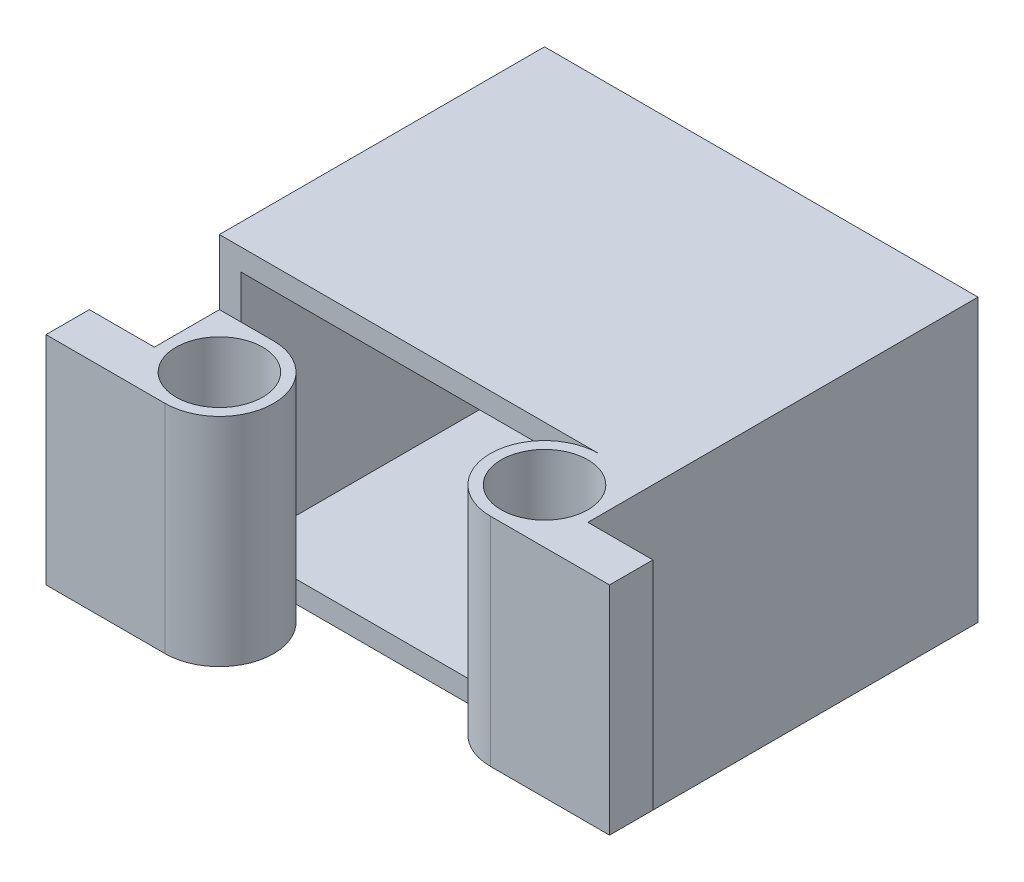
SolidWorks part; units mm, degrees
ref_plane "정면" through (0, 0, 0) normal (0, 0, 1) x (1, 0, 0)
ref_plane "윗면" through (0, 0, 0) normal (0, 1, 0) x (1, 0, 0)
ref_plane "우측면" through (0, 0, 0) normal (1, 0, 0) x (0, 0, -1)
sketch "스케치1" plane through (0, 0, 0) normal (0, 0, 1) x (1, 0, 0)
  line L1 (-10, -6.5) -> (10, -6.5)
  line L2 (-10, -6.5) -> (-10, 6.5)
  line L3 (-10, 6.5) -> (10, 6.5)
  line L4 (10, -6.5) -> (10, 6.5)
  line L5 (-10, -6.5) -> (10, 6.5) construction
  line L6 (-10, 6.5) -> (10, -6.5) construction
  point P0 (0, 0)
  dimension "D1" = 13
  dimension "D2" = 20
extrude "보스-돌출1" add sketch "스케치1" along normal blind 15
shell "쉘1" thickness 1
ref_plane "평면1" through (0, 3.5, 0) normal (0, 1, 0) x (1, 0, 0)
sketch "스케치2" plane through (0, 3.5, 0) normal (0, 1, 0) x (1, 0, 0)
  line L0 (10, -15) -> (-10, -15) construction
  line L2 (-10, -15) -> (-10, 0) construction
  line L3 (-10, -15) -> (-10, -17.5)
  line L5 (-10, -17.5) -> (-10, -20)
  line L6 (-10, -20) -> (-7.5, -20)
  line L9 (-10, -15) -> (-7.5, -15)
  circle A0 centre (-7.5, -17.5) radius 2.5
  circle A2 centre (-7.5, -17.5) radius 2
  dimension "D2" = 5
  dimension "D3" = 4
extrude "보스-돌출4" add sketch "스케치2" against normal blind 10 separate body contours A0 L5 L6 | A0 A2 | A0 L9 L3
sketch "스케치3" plane through (0, 0, 1) normal (0, 0, 1) x (1, 0, 0)
  line L1 (-4.9, 4.9) -> (4.9, 4.9)
  line L2 (-4.9, 4.9) -> (-4.9, -4.9)
  line L3 (-4.9, -4.9) -> (4.9, -4.9)
  line L4 (4.9, 4.9) -> (4.9, -4.9)
  line L5 (-4.9, 4.9) -> (4.9, -4.9) construction
  line L6 (-4.9, -4.9) -> (4.9, 4.9) construction
  circle A0 centre (0, 0) radius 4.9
  dimension "D1" = 9.8
extrude "컷-돌출1" cut sketch "스케치3" against normal blind 0.2 contours A0 L4 L1 | A0 L1 L2 | A0 | A0 L2 L3 | A0 L3 L4
sketch "스케치9" plane through (0, 6.5, 0) normal (0, 1, 0) x (1, 0, 0)
  line L0 (10, -15) -> (10, -17.5)
  line L1 (7.5, -20) -> (10, -20)
  line L2 (10, -20) -> (10, -17.5)
  line L3 (10, -15) -> (7.5, -15)
  circle A0 centre (7.5, -17.5) radius 2.5
  circle A1 centre (7.5, -17.5) radius 2
  line M3 (-10, -15) -> (10, -15)
  dimension "D1" = 5
  dimension "D2" = 4
extrude "보스-돌출8" add sketch "스케치9" against normal blind 10 contours A0 L0 M3 | A0 L1 L2 | A0 A1
sketch "스케치6" plane through (-10, 0, 0) normal (-1, 0, 0) x (0, 0, 1)
  line L0 (15, -6.5) -> (20, -6.5) construction
  line L1 (20, 3.5) -> (18, 3.5)
  line L2 (20, 3.5) -> (20, -6.5)
  line L3 (20, -6.5) -> (18, -6.5)
  line L4 (18, 3.5) -> (18, -6.5)
  line L6 (15, -6.5) -> (20, -6.5) construction
  line L7 (20, -6.5) -> (20, 3.5) construction
  line L8 (15, 3.5) -> (20, 3.5) construction
  dimension "D1" = 2
extrude "보스-돌출10" add sketch "스케치6" along normal blind 3
sketch "스케치10" plane through (10, 0, 0) normal (1, 0, 0) x (0, 0, -1)
  line L0 (-15, -3.5) -> (-20, -3.5) construction
  line L1 (-20, 6.5) -> (-18, 6.5)
  line L2 (-20, 6.5) -> (-20, -3.5)
  line L3 (-20, -3.5) -> (-18, -3.5)
  line L4 (-18, 6.5) -> (-18, -3.5)
  dimension "D1" = 2
extrude "보스-돌출11" add sketch "스케치10" along normal blind 3
